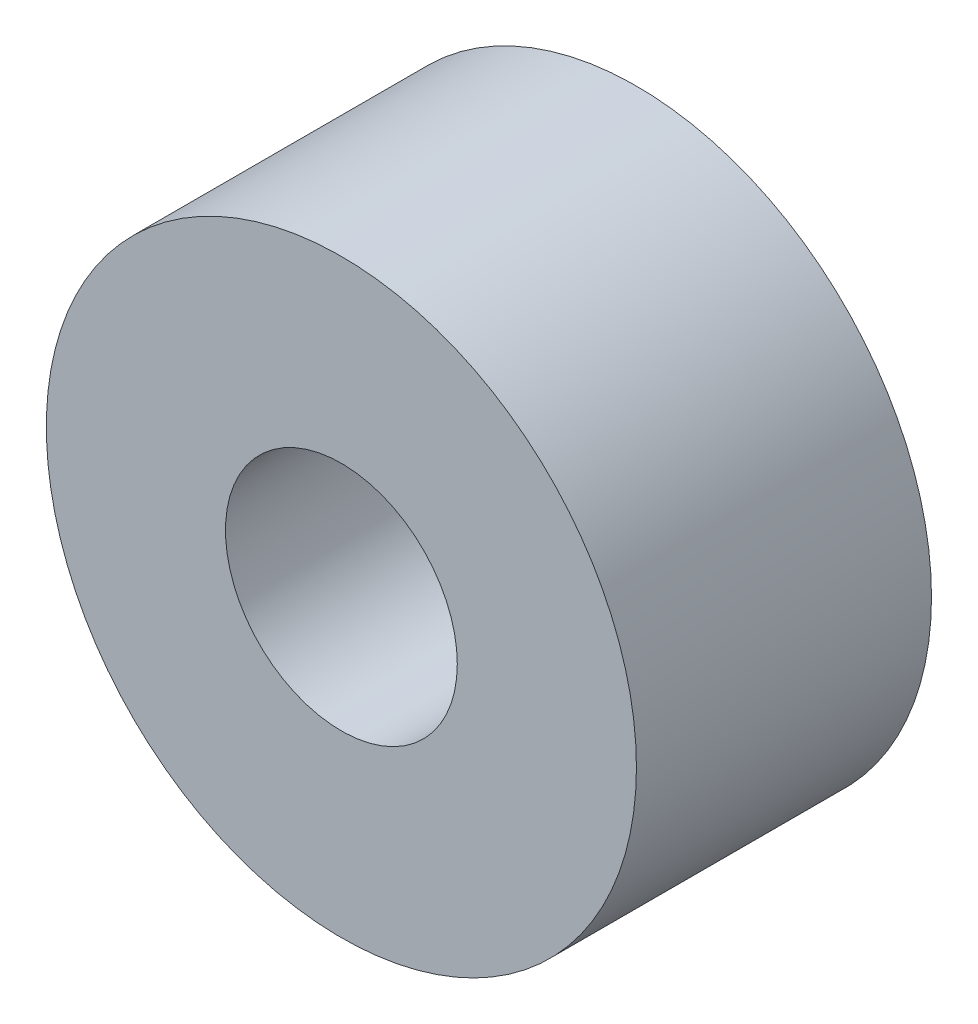
SolidWorks part; units mm, degrees
material "Copper"
ref_plane "Front Plane" through (0, 0, 0) normal (0, 0, 1) x (1, 0, 0)
ref_plane "Top Plane" through (0, 0, 0) normal (0, 1, 0) x (1, 0, 0)
ref_plane "Right Plane" through (0, 0, 0) normal (1, 0, 0) x (0, 0, -1)
sketch "Sketch1" plane through (0, 0, 0) normal (0, 0, 1) x (1, 0, 0)
  circle A0 centre (0, 0) radius 14
  circle A1 centre (0, 0) radius 5.5
  dimension "D1" = 28
  dimension "D2" = 11
extrude "Boss-Extrude1" add sketch "Sketch1" along normal blind 14
